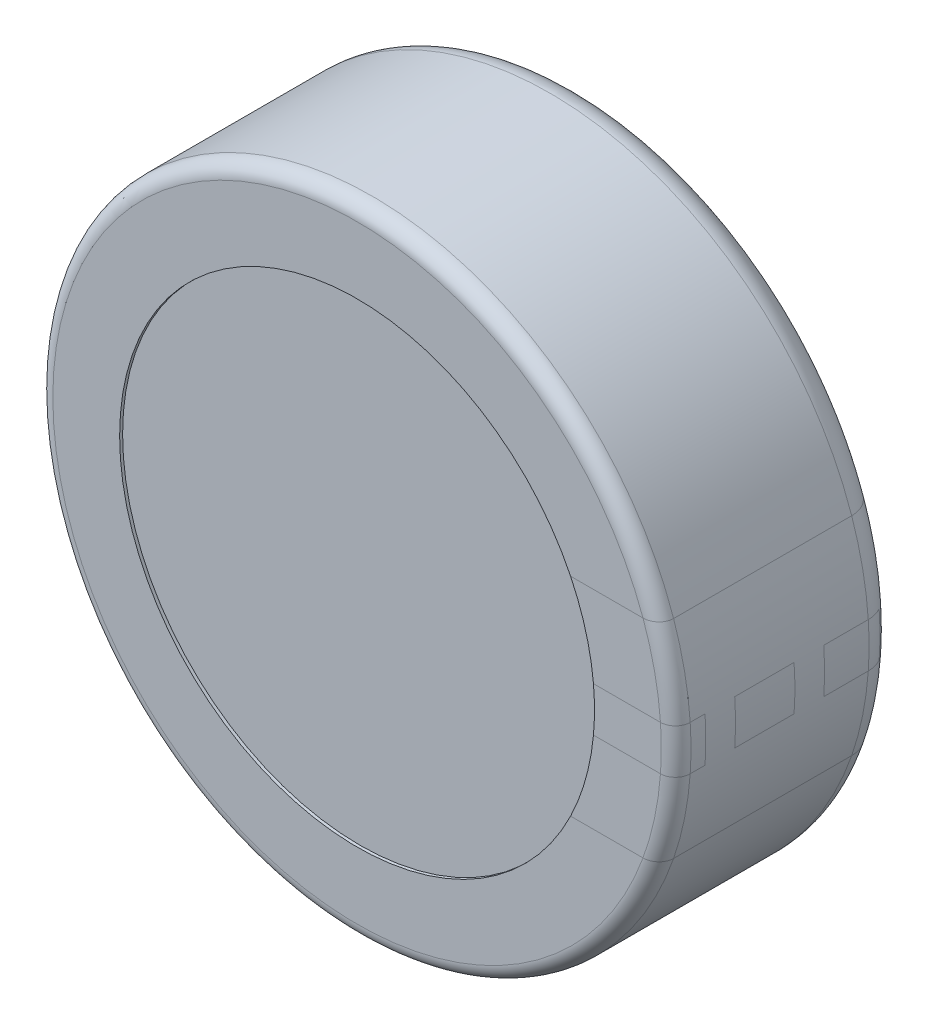
SolidWorks part; units mm, degrees
ref_plane "Front Plane" through (0, 0, 0) normal (0, 0, 1) x (1, 0, 0)
ref_plane "Top Plane" through (0, 0, 0) normal (0, 1, 0) x (1, 0, 0)
ref_plane "Right Plane" through (0, 0, 0) normal (1, 0, 0) x (0, 0, -1)
sketch "Эскиз1" plane through (0, 0, 0) normal (0, 1, 0) x (1, 0, 0)
  line L0 (0, 0) -> (0, -18.187) construction
  line L1 (0, -0.8) -> (-8, -0.8)
  line L2 (-8, -0.8) -> (-8, -0.5)
  line L3 (-8.5, 0) -> (-9.75, 0)
  line L4 (-10.75, -1) -> (-10.75, -7)
  line L6 (-8, -7.5) -> (-8, -7.4)
  line L7 (-8, -7.4) -> (0, -7.4)
  line L8 (0, -7.4) -> (0, -0.8)
  line L9 (-10.25, -7.5) -> (-8, -7.5)
  arc A0 (-8, -0.5) -> (-8.5, 0) centre (-8.5, -0.5) ccw
  arc A1 (-9.75, 0) -> (-10.75, -1) centre (-9.75, -1) ccw
  arc A2 (-10.75, -7) -> (-10.25, -7.5) centre (-10.25, -7) ccw
  point P17 (-9.125, 0)
  dimension "D1" = 1
  dimension "D2" = 0.5
  dimension "D6" = 0.5
  dimension "D3" = 16
  dimension "D4" = 0.8
  dimension "D5" = 21.5
  dimension "D7" = 0.1
  dimension "D8" = 7.5
revolve "Повернуть1" add sketch "Эскиз1" angle 360 about L0
sketch "Эскиз2" plane through (0, 0, 0) normal (1, 0, 0) x (0, 0, -1)
  line L0 (-3.5, 0.75) -> (-3.5, -0.75)
  line L1 (-40.6082, 0) -> (11.1292, 0) construction
  line L3 (0, -3.5) -> (-10.5, -3.5)
  line L4 (0, -3.5) -> (0, 3.5)
  line L5 (-3.5, -0.75) -> (-5.5, -0.75)
  line L6 (0, 3.5) -> (-10.5, 3.5)
  line L7 (-10.5, -3.5) -> (-10.5, 3.5)
  line L8 (-3.5, 0.75) -> (-5.5, 0.75)
  line L9 (-0.5, 0.75) -> (-2.5, 0.75)
  line L10 (-0.5, 0.75) -> (-0.5, -0.75)
  line L11 (-0.5, -0.75) -> (-2.5, -0.75)
  line L12 (-2.5, 0.75) -> (-2.5, -0.75)
  line L13 (-0.5, 0.75) -> (-2.5, -0.75) construction
  line L14 (-0.5, -0.75) -> (-2.5, 0.75) construction
  line L15 (-5.5, 0.75) -> (-5.5, -0.75)
  line L16 (-6.5, 0.75) -> (-6.5, -0.75)
  line L17 (-6.5, -0.75) -> (-8.5, -0.75)
  line L18 (-6.5, 0.75) -> (-8.5, 0.75)
  line L19 (-8.5, 0.75) -> (-8.5, -0.75)
  line L20 (-2.5, 0.75) -> (-3.5, 0.75) construction
  line L21 (-5.5, 0.75) -> (-6.5, 0.75) construction
  point P2 (-10.5, 0)
  point P10 (0, 0)
  point P15 (-1.5, 0)
  point P18 (-6.5, 0)
  point P27 (-3.5, 0)
  point P29 (-5.5, 0)
  point P32 (-8.5, 0)
  dimension "D1" = 7
  dimension "D2" = 2
  dimension "D3" = 1.5
  dimension "D5" = 0.5
  dimension "D4" = 1
  dimension "D6" = 2
split line "Разделяющая линия1"
ref_plane "Плоскость1" through (-2.5, 0, 0) normal (1, 0, 0) x (0, 0, -1)
sketch "Эскиз9" plane through (-2.5, 0, 0) normal (1, 0, 0) x (0, 0, -1)
  line L0 (-0.8, 0.6) -> (-0.8, -0.6)
  line L1 (-0.8, -0.6) -> (1.2711, -0.6)
  line L2 (1.2711, -0.6) -> (1.7, -0.4)
  line L3 (1.7, -0.4) -> (3.8, -0.4)
  line L4 (3.8, 0.4) -> (1.7, 0.4)
  line L5 (1.7, 0.4) -> (1.2711, 0.6)
  line L6 (1.2711, 0.6) -> (-0.8, 0.6)
  line L8 (-0.8, 0.75) -> (-0.8, 3.5) construction
  line L9 (-0.8, 0) -> (4.2, 0) construction
  arc A1 (3.8, -0.4) -> (3.8, 0.4) centre (3.8, 0) ccw
  point P2 (4.2, 0)
  point P8 (0, 0)
  dimension "D1" = 2.5
  dimension "D2" = 5
  dimension "D3" = 0.8
  dimension "D4" = 1.2
  dimension "D5" = 25
extrude "Бобышка-Вытянуть1" add sketch "Эскиз9" along normal mid plane 0.4
fillet "Скругление1" radius 0.1 22 edges at (-2.5, 0.6, 0.8) (-2.5, -0.6, 0.8) (-2.5, -0.6, -1.2711) (-2.5, -0.4, -1.7) (-2.5, 0.4, -1.7) (-2.5, 0.6, -1.2711) (-2.3, 0, 0.8) (-2.3, 0.6, -0.2355) (-2.3, 0.5, -1.4855) (-2.3, 0.4, -2.75) (-2.3, 0, -4.2) (-2.3, -0.4, -2.75) (-2.3, -0.5, -1.4855) (-2.3, -0.6, -0.2355) (-2.7, -0.5, -1.4855) (-2.7, -0.4, -2.75) (-2.7, 0, -4.2) (-2.7, 0.4, -2.75) (-2.7, 0.5, -1.4855) (-2.7, 0.6, -0.2355) (-2.7, 0, 0.8) (-2.7, -0.6, -0.2355)
mirror "Зеркальное отражение1" about plane through (0, 0, 0) normal (1, 0, 0) of "Скругление1", "Бобышка-Вытянуть1"
sketch "Эскиз10" plane through (0, 0, 0.8) normal (0, 0, -1) x (-1, 0, 0)
  line L0 (2.5, 8.8638) -> (2.5, -8.8638) construction
  line L2 (-8, 1.75) -> (-2.4, 1.75)
  line L3 (-2.4, 1.75) -> (-2.4, -1.75)
  line L4 (-2.4, -1.75) -> (-8, -1.75)
  line L5 (-8, -1.75) -> (-8, 1.75)
  line L6 (2.5, 0) -> (-2.4, 0) construction
  circle A0 centre (2.5, 0) radius 1.75
  arc A1 (-7.9648, 0.75) -> (-7.9648, -0.75) centre (0, 0) ccw construction
  dimension "D1" = 3.5
  dimension "D2" = 3.5
extrude "Бобышка-Вытянуть2" add sketch "Эскиз10" along normal blind 0.1
